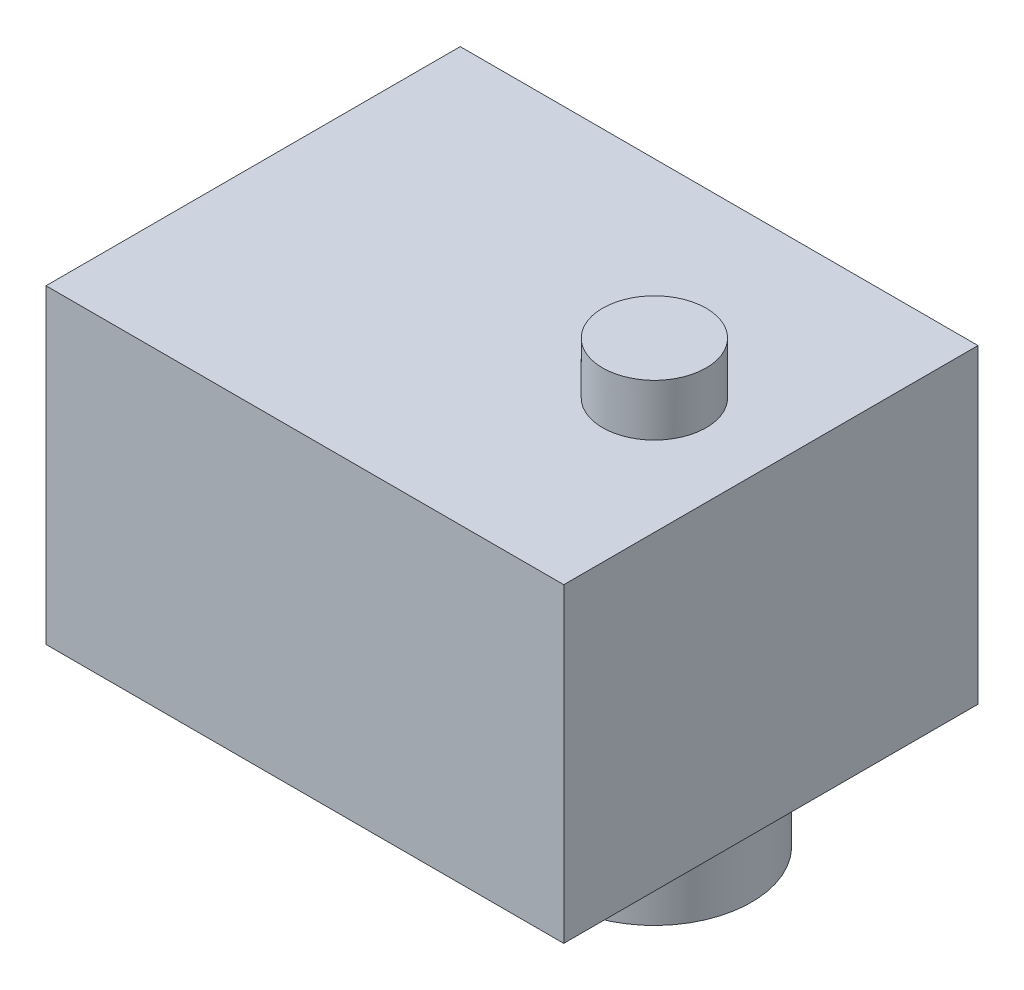
SolidWorks part; units mm, degrees
ref_plane "Спереди" through (0, 0, 0) normal (0, 0, 1) x (1, 0, 0)
ref_plane "Сверху" through (0, 0, 0) normal (0, 1, 0) x (1, 0, 0)
ref_plane "Справа" through (0, 0, 0) normal (1, 0, 0) x (0, 0, -1)
sketch "Эскиз1" plane through (0, 0, 0) normal (0, 1, 0) x (1, 0, 0)
  line L1 (0, 0) -> (20, 0)
  line L2 (0, 0) -> (0, 16)
  line L3 (0, 16) -> (20, 16)
  line L4 (20, 0) -> (20, 16)
  dimension "D1" = 16
  dimension "D2" = 20
extrude "Бобышка-Вытянуть1" add sketch "Эскиз1" along normal blind 12
sketch "Эскиз2" plane through (0, 12, 0) normal (0, 1, 0) x (1, 0, 0)
  line L0 (20, 0) -> (20, 16) construction
  line L1 (0, 0) -> (20, 0) construction
  circle A0 centre (15.5, 8) radius 2
  dimension "D1" = 4.5
  dimension "D3" = 4
  dimension "D2" = 8
extrude "Бобышка-Вытянуть2" add sketch "Эскиз2" along normal blind 2
sketch "Эскиз3" plane through (0, 0, 0) normal (0, -1, 0) x (1, 0, 0)
  line L0 (20, 0) -> (20, -16) construction
  line L1 (20, -16) -> (0, -16) construction
  circle A0 centre (15.5, -8) radius 3.75
  dimension "D1" = 7.5
  dimension "D2" = 4.5
  dimension "D3" = 8
extrude "Бобышка-Вытянуть3" add sketch "Эскиз3" along normal blind 3
sketch "Эскиз4" plane through (0, -3, 0) normal (0, -1, 0) x (1, 0, 0)
  circle A0 centre (15.5, -8) radius 2
extrude "Бобышка-Вытянуть4" add sketch "Эскиз4" along normal blind 2 draft 30
